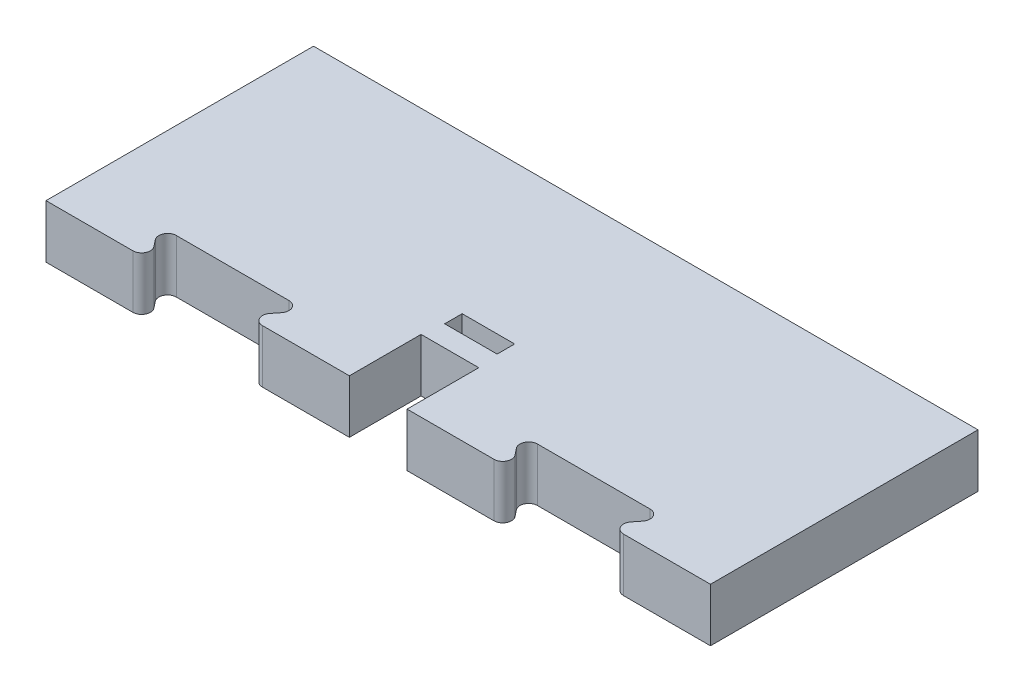
SolidWorks part; units mm, degrees
ref_plane "Front Plane" through (0, 0, 0) normal (0, 0, 1) x (1, 0, 0)
ref_plane "Top Plane" through (0, 0, 0) normal (0, 1, 0) x (1, 0, 0)
ref_plane "Right Plane" through (0, 0, 0) normal (1, 0, 0) x (0, 0, -1)
sketch "Sketch1" plane through (0, 0, 0) normal (0, 1, 0) x (1, 0, 0)
  line L0 (0, 0) -> (38, 0)
  line L1 (0, 0) -> (0, 8.3)
  line L2 (38, 0) -> (38, 8.3)
  line L3 (0, 8.3) -> (38, 8.3)
  dimension "D1" = 8.3
  dimension "D2" = 38
extrude "Boss-Extrude1" add sketch "Sketch1" along normal blind 3.05
sketch "Sketch3" plane through (0, 3.05, 0) normal (0, 1, 0) x (1, 0, 0)
  line L0 (19, 8.3) -> (19, 6.3)
  line L1 (38, 8.3) -> (0, 8.3) construction
  line L2 (20.5, 6.3) -> (17.5, 6.3)
  line L3 (17.5, 6.3) -> (17.5, 5.3)
  line L4 (17.5, 5.3) -> (20.5, 5.3)
  line L5 (20.5, 5.3) -> (20.5, 6.3)
  line L6 (19, 5.3) -> (19, 4.1)
  line L7 (20.65, 4.1) -> (17.35, 4.1)
  line L8 (17.35, 4.1) -> (17.35, 0)
  line L9 (0, 0) -> (38, 0) construction
  line L10 (17.35, 0) -> (20.65, 0)
  line L11 (20.65, 0) -> (20.65, 4.1)
  point P7 (19, 6.3)
  point P14 (19, 4.1)
  line M9 (0, 0) -> (38, 0)
  dimension "D1" = 2
  dimension "D2" = 1
  dimension "D3" = 1.2
  dimension "D4" = 3.3
  dimension "D5" = 3
extrude "Cut-Extrude2" cut sketch "Sketch3" against normal through all contours L11 L7 L8 M9 | L4 L5 L2 L3
sketch "Sketch2" plane through (0, 3.05, 0) normal (0, 1, 0) x (1, 0, 0)
  line L0 (0, 0) -> (0, 2)
  line L1 (0, 8.3) -> (0, 0) construction
  line L2 (0, 2) -> (38, 2) construction
  line L3 (38, 0) -> (38, 8.3) construction
  line L4 (0, 0) -> (6, 0)
  line L5 (0, 0) -> (17.35, 0) construction
  line L6 (6, 0) -> (4.425, 2)
  line L7 (4.425, 2) -> (12.925, 2)
  line L8 (12.925, 2) -> (11.35, 0)
  line L9 (11.35, 0) -> (17.35, 0)
  line L10 (26.65, 0) -> (25.075, 2)
  line L11 (25.075, 2) -> (33.575, 2)
  line L12 (33.575, 2) -> (32, 0)
  line L13 (32, 0) -> (38, 0)
  line L14 (6, 0) -> (11.35, 0)
  line L15 (26.65, 0) -> (32, 0)
  line L16 (0, 2) -> (4.425, 2)
  line L17 (33.575, 2) -> (38, 2)
  line L18 (38, 2) -> (38, 0)
  line L19 (20.65, 0) -> (26.65, 0)
  line L20 (12.925, 2) -> (17.35, 2)
  line L21 (17.35, 4.1) -> (17.35, 0) construction
  line L22 (17.35, 2) -> (17.35, 0)
  line L23 (20.65, 0) -> (20.65, 2)
  line L24 (20.65, 0) -> (20.65, 4.1) construction
  line L25 (20.65, 2) -> (25.075, 2)
  dimension "D1" = 2
  dimension "D2" = 6
  dimension "D4" = 8.5
extrude "Cut-Extrude1" cut sketch "Sketch2" against normal through all
fillet "Fillet1" radius 0.5 8 edges at (32, 1.525, 0) (26.65, 1.525, 0) (11.35, 1.525, 0) (6, 1.525, 0) (25.075, 1.525, -2) (33.575, 1.525, -2) (12.925, 1.525, -2) (4.425, 1.525, -2)
sketch "Sketch4" plane through (0, 0, -8.3) normal (0, 0, -1) x (-1, 0, 0)
  line L0 (-38, 3.05) -> (0, 3.05)
  line L1 (-38, 3.05) -> (-38, 0)
  line L2 (0, 3.05) -> (0, 0)
  line L3 (-38, 0) -> (0, 0)
extrude "Boss-Extrude2" add sketch "Sketch4" along normal blind 7
